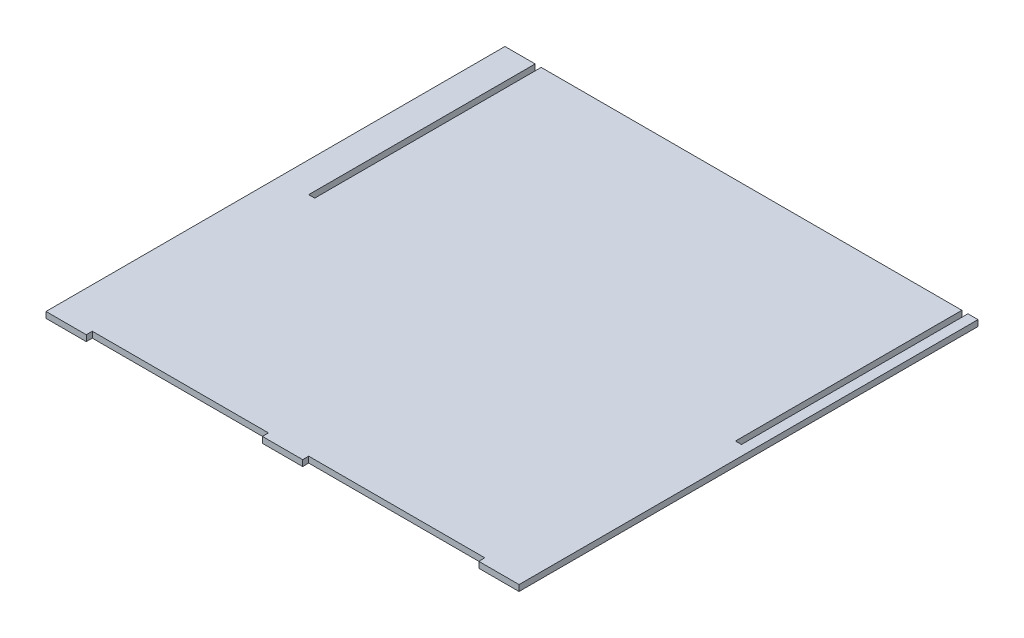
SolidWorks part; units mm, degrees
ref_plane "Front Plane" through (0, 0, 0) normal (0, 0, 1) x (1, 0, 0)
ref_plane "Top Plane" through (0, 0, 0) normal (0, 1, 0) x (1, 0, 0)
ref_plane "Right Plane" through (0, 0, 0) normal (1, 0, 0) x (0, 0, -1)
sketch "Sketch1" plane through (0, 0, 0) normal (0, 1, 0) x (1, 0, 0)
  line L0 (-470, 0) -> (-430, 0)
  line L2 (0, 0) -> (0, 456)
  line L3 (0, 456) -> (-470, 456)
  line L4 (-470, 0) -> (-470, 456)
  line L5 (-430, 0) -> (-430, 6)
  line L6 (0, 0) -> (-40, 0)
  line L7 (-40, 0) -> (-40, 6)
  line L8 (-40, 6) -> (-215, 6)
  line L9 (-215, 6) -> (-215, 0)
  line L10 (-215, 0) -> (-255, 0)
  line L11 (-255, 0) -> (-255, 6)
  line L12 (-255, 6) -> (-430, 6)
  dimension "D1" = 470
  dimension "D2" = 456
  dimension "D3" = 40
  dimension "D4" = 6
extrude "Boss-Extrude1" add sketch "Sketch1" along normal blind 6 contours L4 L3 L2 L6 L7 L8 L9 L10 L11 L12 L5 L0
sketch "Sketch2" plane through (0, 6, 0) normal (0, 1, 0) x (1, 0, 0)
  line L1 (-10, 456) -> (-16, 456)
  line L2 (-10, 456) -> (-10, 231)
  line L3 (-10, 231) -> (-16, 231)
  line L4 (-16, 456) -> (-16, 231)
  line L6 (0, 0) -> (0, 456) construction
  line L7 (0, 456) -> (-470, 456) construction
  dimension "D1" = 6
  dimension "D2" = 10
  dimension "D3" = 225
extrude "Cut-Extrude1" cut sketch "Sketch2" against normal blind 6
pattern_linear "LPattern1" count 2 spacing 424 along (-1, 0, 0) of "Cut-Extrude1"
